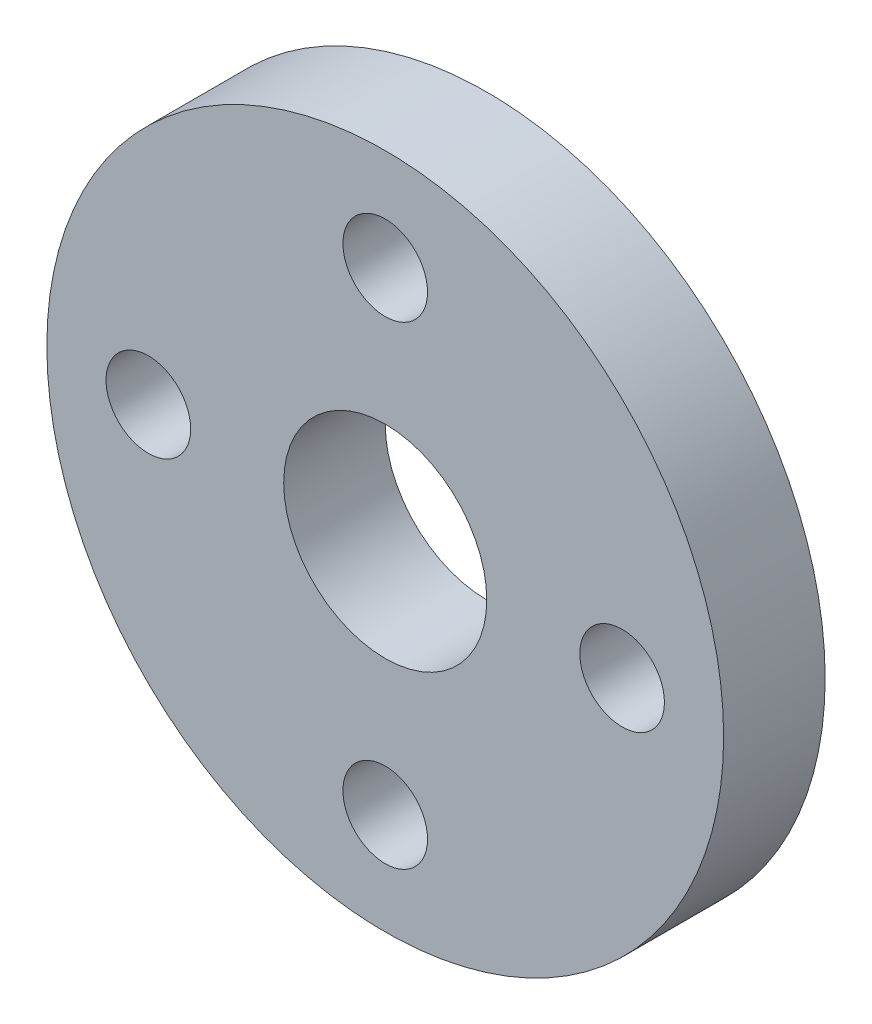
SolidWorks part; units mm, degrees
ref_plane "前视基准面" through (0, 0, 0) normal (0, 0, 1) x (1, 0, 0)
ref_plane "上视基准面" through (0, 0, 0) normal (0, 1, 0) x (1, 0, 0)
ref_plane "右视基准面" through (0, 0, 0) normal (1, 0, 0) x (0, 0, -1)
sketch "草图1" plane through (0, 0, 0) normal (0, 0, 1) x (1, 0, 0)
  circle A0 centre (0, 0) radius 10
  circle A1 centre (0, 0) radius 3
  circle A2 centre (0, 0) radius 7 construction
  point P16 (0, 0)
  point P23 (0, 0)
  dimension "D1" = 20
  dimension "D2" = 14
extrude "凸台-拉伸1" add sketch "草图1" along normal blind 3
sketch "草图2" plane through (0, 0, 3) normal (0, 0, 1) x (1, 0, 0)
  circle A0 centre (0, 0) radius 7 construction
  circle A1 centre (0, 7) radius 1.5
  circle A2 centre (7, 0) radius 1.5
  circle A3 centre (0, -7) radius 1.5
  circle A4 centre (-7, 0) radius 1.5
  point P14 (0, 0)
  dimension "D1" = 14
  dimension "D2" = 3
  dimension "D3" = 4
hole_wizard "M3 螺纹孔1" positions "3D草图1" profile "草图3" tap size "M3" standard "GB" end condition through all
sketch3d "3D草图1"
  point P0 (0, 7, 3)
  point P3 (-7, 0, 3)
  point P6 (0, -7, 3)
  point P9 (7, 0, 3)
sketch "草图3" plane through (0, 7, 3) normal (1, 0, 0) x (0, -1, 0)
  line L0 (0, 0) -> (0, 3)
  line L1 (0, 3) -> (1.25, 3)
  line L2 (1.25, 3) -> (1.25, 0)
  line L5 (1.25, 0) -> (0, 0)
  line L11 (0, -6.35) -> (0, 107.95) construction
  dimension "通孔螺纹孔钻头直径" = 2.5
  dimension "通孔螺纹孔钻头深度" = 3
cosmetic thread "孔螺蚊线1" parameters "D2"=3
cosmetic thread "孔螺蚊线2" parameters "D2"=3
cosmetic thread "孔螺蚊线3" parameters "D2"=3
cosmetic thread "孔螺蚊线4" parameters "D2"=3
